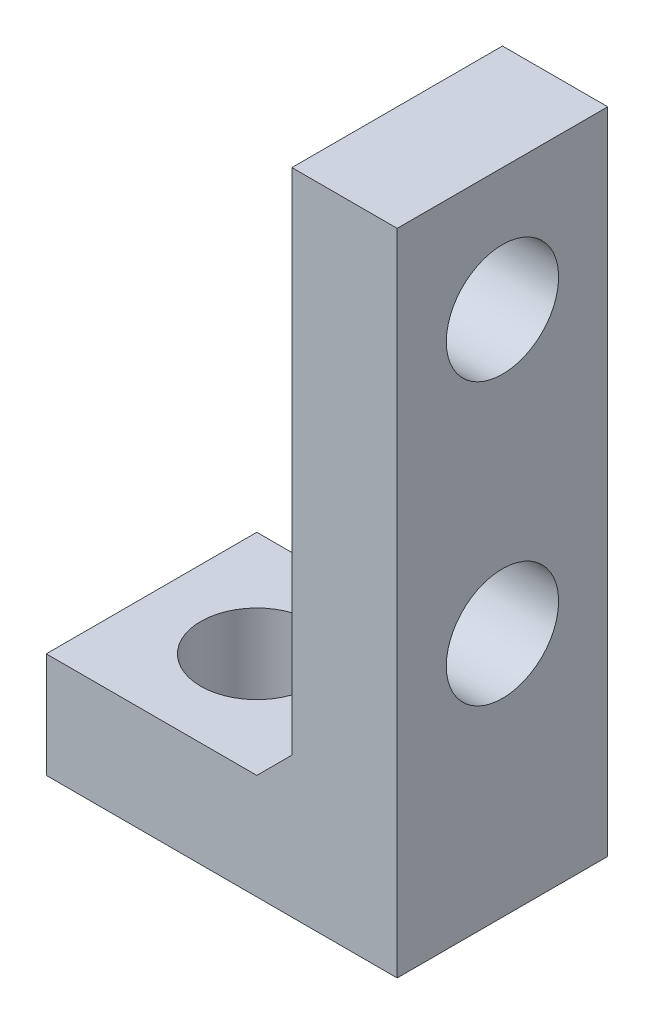
SolidWorks part; units mm, degrees
ref_plane "Front Plane" through (0, 0, 0) normal (0, 0, 1) x (1, 0, 0)
ref_plane "Top Plane" through (0, 0, 0) normal (0, 1, 0) x (1, 0, 0)
ref_plane "Right Plane" through (0, 0, 0) normal (1, 0, 0) x (0, 0, -1)
sketch "Sketch1" plane through (0, 0, 0) normal (0, 1, 0) x (1, 0, 0)
  line L1 (-5, -3) -> (5, -3)
  line L2 (-5, -3) -> (-5, 3)
  line L3 (-5, 3) -> (5, 3)
  line L4 (5, -3) -> (5, 3)
  line L5 (0, 3) -> (0, -3) construction
  line L6 (-5, 0) -> (5, 0) construction
  circle A0 centre (-2, 0) radius 1.6
  point P0 (0, 0)
  dimension "D4" = 3.2
  dimension "D1" = 10
  dimension "D2" = 6
  dimension "D3" = 3
extrude "Boss-Extrude1" add sketch "Sketch1" along normal blind 3
sketch "Sketch2" plane through (0, 3, 0) normal (0, 1, 0) x (1, 0, 0)
  line L0 (5, 3) -> (5, -3)
  line L1 (5, 3) -> (2, 3)
  line L2 (5, -3) -> (2, -3)
  line L3 (2, 3) -> (2, -3)
  dimension "D1" = 3
extrude "Boss-Extrude2" add sketch "Sketch2" along normal blind 15.5
sketch "Sketch3" plane through (2, 0, 0) normal (-1, 0, 0) x (0, 0, 1)
  line L0 (0, 18.5) -> (0, 3) construction
  line L1 (-3, 18.5) -> (3, 18.5) construction
  line L2 (-3, 3) -> (3, 3) construction
  circle A0 centre (0, 7) radius 1.6
  circle A1 centre (0, 15) radius 1.6
  dimension "D1" = 3.2
  dimension "D4" = 8
  dimension "D2" = 4
  dimension "D3" = 2
extrude "Cut-Extrude1" cut sketch "Sketch3" against normal through all
ref_plane "Plane1" through (2, 3, 3) normal (0, 0, 1) x (1, 0, 0)
sketch "Sketch5" plane through (2, 3, 3) normal (0, 0, 1) x (1, 0, 0)
  line L0 (-1, 0) -> (0, 1)
  line L1 (-7, 0) -> (0, 0) construction
  line L2 (0, 15.5) -> (0, 0) construction
  line L3 (0, 1) -> (0, 0)
  line L4 (0, 0) -> (-1, 0)
  dimension "D1" = 135
  dimension "D2" = 1
extrude "Boss-Extrude3" add sketch "Sketch5" against normal blind 6
